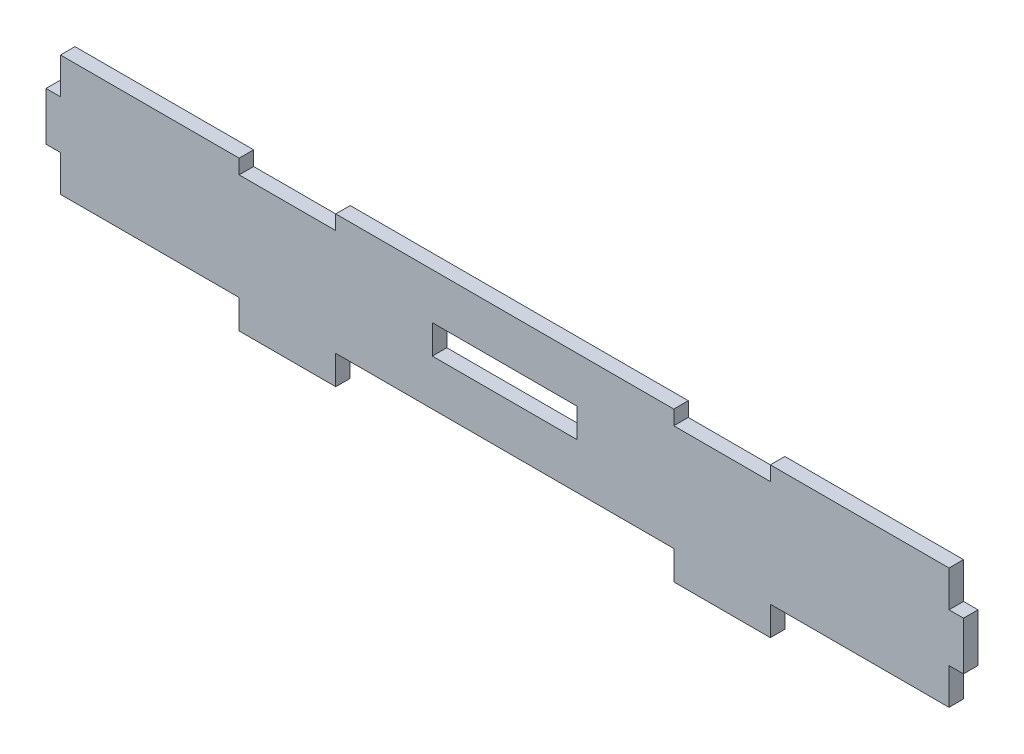
SolidWorks part; units mm, degrees
ref_plane "Спереди" through (0, 0, 0) normal (0, 0, 1) x (1, 0, 0)
ref_plane "Сверху" through (0, 0, 0) normal (0, 1, 0) x (1, 0, 0)
ref_plane "Справа" through (0, 0, 0) normal (1, 0, 0) x (0, 0, -1)
sketch "Эскиз1" plane through (0, 0, 0) normal (0, 0, 1) x (1, 0, 0)
  line L0 (57, 25) -> (127, 25)
  line L1 (0, 0) -> (37, 0)
  line L2 (0, 0) -> (0, 7.5)
  line L3 (0, 25) -> (37, 25)
  line L4 (184, 0) -> (184, 7.5)
  line L6 (37, 0) -> (37, -6)
  line L7 (37, -6) -> (57, -6)
  line L8 (57, 0) -> (57, -6)
  line L10 (127, 0) -> (127, -6)
  line L11 (127, -6) -> (147, -6)
  line L12 (147, 0) -> (147, -6)
  line L13 (184, 17.5) -> (187, 17.5)
  line L14 (-3, 17.5) -> (0, 17.5)
  line L15 (-3, 17.5) -> (-3, 7.5)
  line L16 (-3, 7.5) -> (0, 7.5)
  line L19 (184, 7.5) -> (187, 7.5)
  line L20 (187, 17.5) -> (187, 7.5)
  line L22 (37, 25) -> (37, 22)
  line L23 (37, 22) -> (57, 22)
  line L24 (57, 25) -> (57, 22)
  line L26 (127, 25) -> (127, 22)
  line L27 (127, 22) -> (147, 22)
  line L28 (147, 25) -> (147, 22)
  line L29 (147, 25) -> (184, 25)
  line L30 (147, 0) -> (184, 0)
  line L31 (57, 0) -> (127, 0)
  line L32 (0, 17.5) -> (0, 25)
  line L33 (184, 17.5) -> (184, 25)
  line L35 (77, 15.5) -> (107, 15.5)
  line L36 (77, 15.5) -> (77, 9.5)
  line L37 (77, 9.5) -> (107, 9.5)
  line L38 (107, 15.5) -> (107, 9.5)
  point P29 (57, 23.5)
  point P34 (77, 12.5)
  point P35 (-3, 12.5)
  dimension "D1" = 25
  dimension "D2" = 184
  dimension "D3" = 20
  dimension "D4" = 20
  dimension "D5" = 6
  dimension "D6" = 3
  dimension "D7" = 3
  dimension "D8" = 3
  dimension "D9" = 37
  dimension "D10" = 70
  dimension "D11" = 10
  dimension "D12" = 7.5
  dimension "D13" = 20
  dimension "D14" = 20
  dimension "D15" = 6
extrude "Бобышка-Вытянуть1" add sketch "Эскиз1" along normal blind 3
